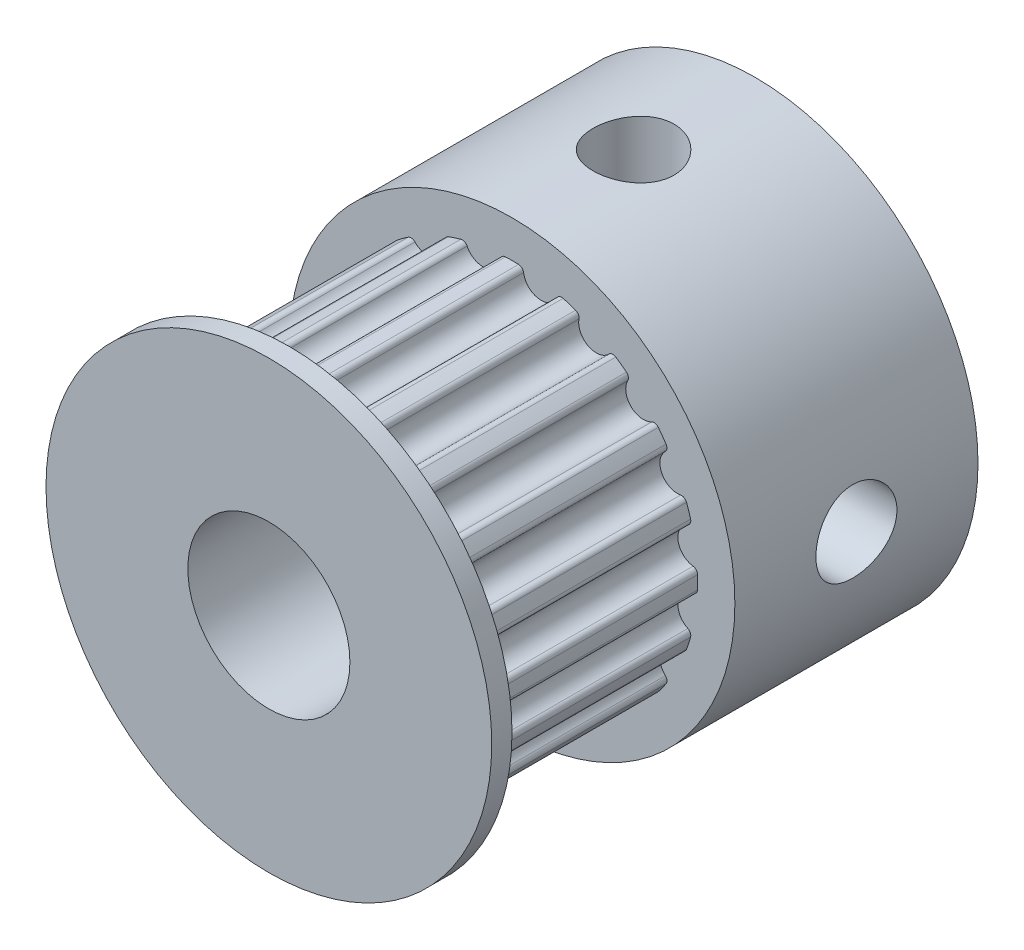
SolidWorks part; units mm, degrees
material "6061 Alloy"
ref_plane "Front Plane" through (0, 0, 0) normal (0, 0, 1) x (1, 0, 0)
ref_plane "Top Plane" through (0, 0, 0) normal (0, 1, 0) x (1, 0, 0)
ref_plane "Right Plane" through (0, 0, 0) normal (1, 0, 0) x (0, 0, -1)
sketch "Sketch1" plane through (0, 0, 0) normal (0, 0, 1) x (1, 0, 0)
  circle A0 centre (0, 0) radius 9.5493 construction
  circle A1 centre (0, 0) radius 9.1683
  dimension "D1" = 19.0986
  dimension "D2" = 0.381
extrude "Boss-Extrude1" add sketch "Sketch1" along normal mid plane 11
sketch "Sketch2" plane through (0, 0, 5.5) normal (0, 0, 1) x (1, 0, 0)
  line L0 (0, 0) -> (0, 9.1683) construction
  line L1 (0, 0) -> (1.4342, 9.0554) construction
  line L2 (0, 0) -> (-1.4342, 9.0554) construction
  line L3 (-1.2981, 8.1961) -> (-1.4342, 9.0554)
  line L4 (-1.4342, 9.0554) -> (-1.4342, 10.5021)
  line L5 (-1.4342, 10.5021) -> (1.4342, 10.5021)
  line L6 (1.4342, 10.5021) -> (1.4342, 9.0554)
  line L7 (1.4342, 9.0554) -> (1.2981, 8.1961)
  circle A0 centre (0, 0) radius 9.1683 construction
  circle A1 centre (1.4342, 9.0554) radius 0.87 construction
  circle A2 centre (-1.4342, 9.0554) radius 0.87 construction
  circle A3 centre (0.3146, 8.9027) radius 0.26 construction
  circle A4 centre (-0.3146, 8.9027) radius 0.26 construction
  circle A5 centre (0, 0) radius 9.1683 construction
  arc A6 (-0.3238, 9.1626) -> (0.3238, 9.1626) centre (0, 0) cw
  arc A7 (0.3238, 9.1626) -> (0.5722, 8.9379) centre (0.3146, 8.9027) cw
  arc A8 (0.5722, 8.9379) -> (1.2981, 8.1961) centre (1.4342, 9.0554) ccw
  arc A9 (-0.5722, 8.9379) -> (-1.2981, 8.1961) centre (-1.4342, 9.0554) cw
  arc A10 (-0.5722, 8.9379) -> (-0.3238, 9.1626) centre (-0.3146, 8.9027) cw
  dimension "D3" = 1.74
  dimension "D4" = 0.52
  dimension "D1" = 9
  dimension "D2" = 9
extrude "Cut-Extrude1" cut sketch "Sketch2" against normal through all both and the other way through all
pattern_circular "CirPattern1" count 20 over 360 about axis through (0, 0, 0) along (0, 0, 1) of "Cut-Extrude1"
sketch "Sketch3" plane through (0, 0, 5.5) normal (0, 0, 1) x (1, 0, 0)
  circle A0 centre (0, 0) radius 11
  dimension "D1" = 22
extrude "Boss-Extrude2" add sketch "Sketch3" along normal blind 1
sketch "Sketch4" plane through (0, 0, -5.5) normal (0, 0, -1) x (-1, 0, 0)
  circle A0 centre (0, 0) radius 11
  dimension "D1" = 22
extrude "Boss-Extrude3" add sketch "Sketch4" along normal blind 12
sketch "Sketch6" plane through (0, 0, 6.5) normal (0, 0, 1) x (1, 0, 0)
  circle A0 centre (0, 0) radius 4
  dimension "D1" = 8
extrude "Cut-Extrude2" cut sketch "Sketch6" against normal through all
sketch "Sketch7" plane through (0, 0, 0) normal (1, 0, 0) x (0, 0, -1)
  line L0 (11.5, 11) -> (11.5, -11) construction
  line L1 (17.5, 11) -> (5.5, 11) construction
  line L2 (5.5, -11) -> (17.5, -11) construction
  circle A0 centre (11.5, 0) radius 2
  dimension "D1" = 4
extrude "Cut-Extrude3" cut sketch "Sketch7" along normal through all
pattern_circular "CirPattern2" count 2 every 90 about axis through (0, 0, -17.5) along (0, 0, 1) of "Cut-Extrude3"
